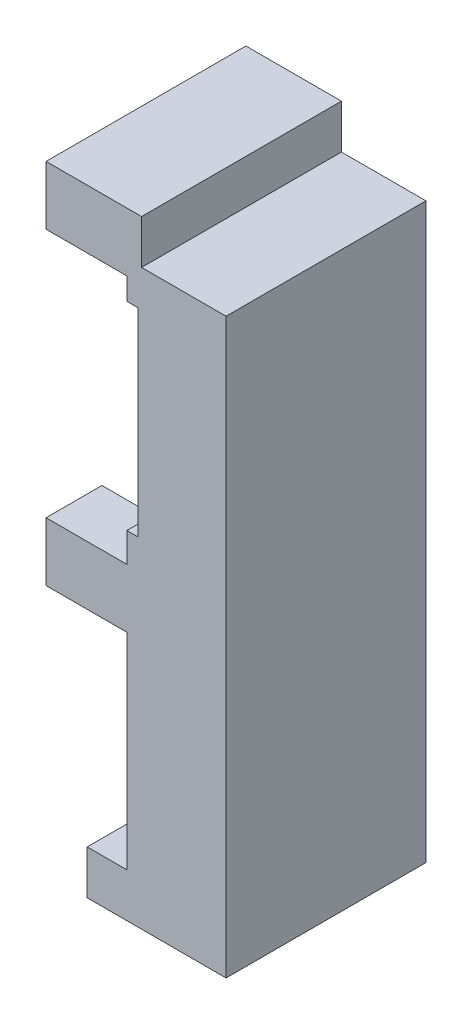
SolidWorks part; units mm, degrees
ref_plane "前视基准面" through (0, 0, 0) normal (0, 0, 1) x (1, 0, 0)
ref_plane "上视基准面" through (0, 0, 0) normal (0, 1, 0) x (1, 0, 0)
ref_plane "右视基准面" through (0, 0, 0) normal (1, 0, 0) x (0, 0, -1)
other "Configuration Table"
sketch "草图1" plane through (0, 0, 0) normal (0, 0, 1) x (1, 0, 0)
  line L0 (10.2, 0) -> (16.95, 0)
  line L1 (16.95, 0) -> (16.95, 54)
  line L2 (16.95, 54) -> (11.2, 54)
  line L3 (11.2, 54) -> (11.2, 57)
  line L4 (11.2, 57) -> (4.7, 57)
  line L5 (4.7, 57) -> (4.7, 53)
  line L6 (4.7, 53) -> (10.2, 53)
  line L7 (10.2, 53) -> (10.2, 51.5)
  line L8 (10.2, 51.5) -> (10.95, 51.5)
  line L9 (10.95, 51.5) -> (10.95, 38)
  line L10 (10.95, 38) -> (10.2, 38)
  line L11 (10.2, 38) -> (10.2, 36)
  line L12 (10.2, 36) -> (4.7, 36)
  line L13 (4.7, 36) -> (4.7, 32)
  line L14 (4.7, 32) -> (10.2, 32)
  line L15 (10.2, 32) -> (10.2, 0)
  dimension "x0" = 10.2
  dimension "x1" = 16.95
  dimension "x3" = 11.2
  dimension "x5" = 4.7
  dimension "x7" = 10.2
  dimension "x9" = 10.95
  dimension "x11" = 10.2
  dimension "x13" = 4.7
  dimension "y2" = 54
  dimension "y4" = 57
  dimension "y6" = 53
  dimension "y8" = 51.5
  dimension "y10" = 38
  dimension "y12" = 36
  dimension "y14" = 32
extrude "Guide_and_solid_stops" add sketch "草图1" along normal blind 13.6
ref_plane "Channel_midplane" through (0, 0, 6.8) normal (0, 0, 1) x (1, 0, 0)
sketch "草图3" plane through (0, 0, 6.8) normal (0, 0, 1) x (1, 0, 0)
  line L0 (7, 37.5) -> (15.4, 37.5)
  line L1 (15.4, 37.5) -> (15.4, 51.5)
  line L2 (15.4, 51.5) -> (7, 51.5)
  line L3 (7, 51.5) -> (7, 37.5)
  dimension "x0" = 7
  dimension "x1" = 15.4
  dimension "y0" = 37.5
  dimension "y2" = 51.5
extrude "Nut_tongue_channel" cut sketch "草图3" against normal mid plane 5.6
sketch "草图4" plane through (0, 0, 6.8) normal (0, 0, 1) x (1, 0, 0)
  line L0 (4, 31) -> (10.25, 31)
  line L1 (10.25, 31) -> (10.25, 36.2)
  line L2 (10.25, 36.2) -> (4, 36.2)
  line L3 (4, 36.2) -> (4, 31)
  dimension "x0" = 4
  dimension "x1" = 10.25
  dimension "y0" = 31
  dimension "y2" = 36.2
extrude "Lower_yoke_relief" cut sketch "草图4" against normal mid plane 6
sketch "草图5" plane through (0, 0, 0) normal (0, 0, 1) x (1, 0, 0)
  line L0 (7.5, 15) -> (11.2, 15)
  line L1 (11.2, 15) -> (11.2, 18)
  line L2 (11.2, 18) -> (7.5, 18)
  line L3 (7.5, 18) -> (7.5, 15)
  dimension "x0" = 7.5
  dimension "x1" = 11.2
  dimension "y0" = 15
  dimension "y2" = 18
extrude "Lower_inward_stop" add sketch "草图5" along normal blind 3.8
ref_plane "Lower_stop_rear_plane" through (0, 0, 9.8) normal (0, 0, 1) x (1, 0, 0)
sketch "草图7" plane through (0, 0, 9.8) normal (0, 0, 1) x (1, 0, 0)
  line L0 (7.5, 15) -> (11.2, 15)
  line L1 (11.2, 15) -> (11.2, 18)
  line L2 (11.2, 18) -> (7.5, 18)
  line L3 (7.5, 18) -> (7.5, 15)
  dimension "x0" = 7.5
  dimension "x1" = 11.2
  dimension "y0" = 15
  dimension "y2" = 18
extrude "凸台-拉伸2" add sketch "草图7" along normal blind 3.8
sketch "草图8" plane through (0, 0, 0) normal (0, 0, 1) x (1, 0, 0)
  line L0 (3, -2) -> (20, -2)
  line L1 (20, -2) -> (20, 15)
  line L2 (20, 15) -> (3, 15)
  line L3 (3, 15) -> (3, -2)
  dimension "x0" = 3
  dimension "x1" = 20
  dimension "y0" = 2
  dimension "y2" = 15
extrude "Remove_lower_tail" cut sketch "草图8" against normal through all and the other way through all
